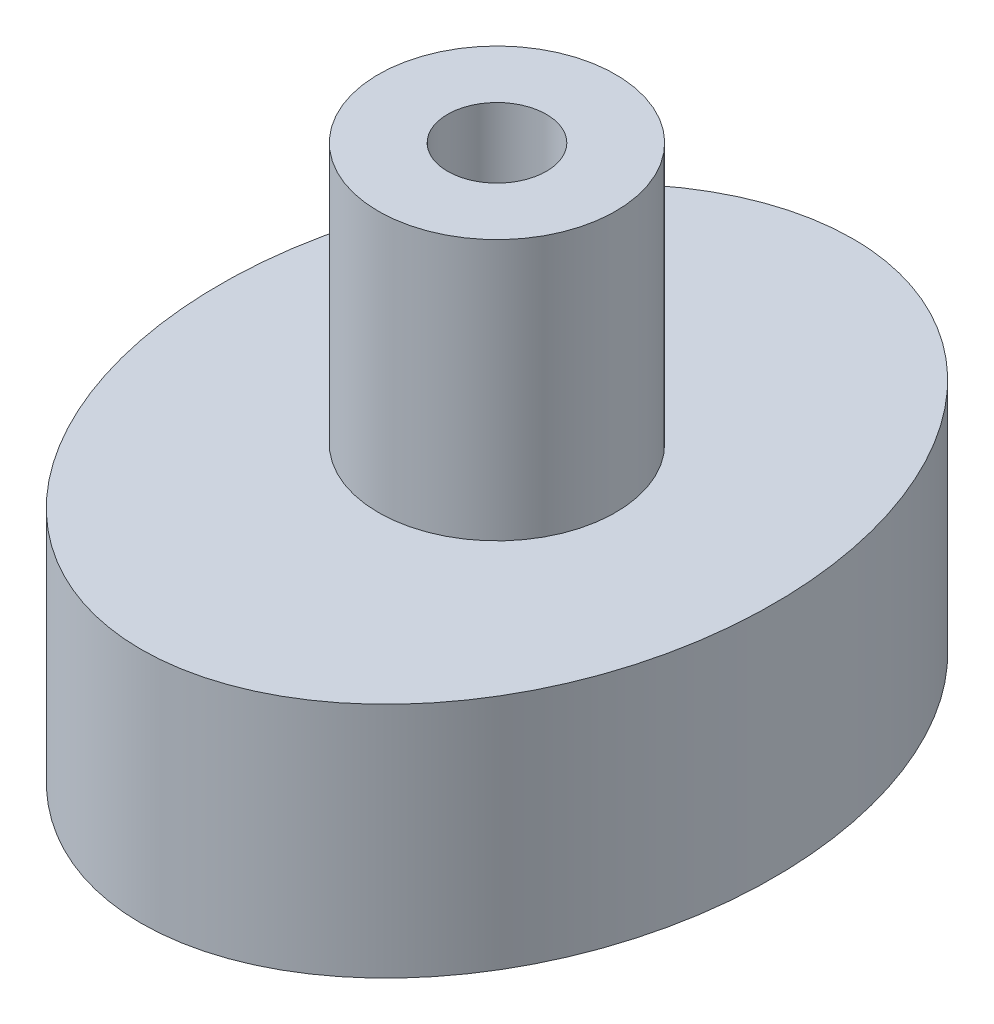
SolidWorks part; units mm, degrees
ref_plane "Front Plane" through (0, 0, 0) normal (0, 0, 1) x (1, 0, 0)
ref_plane "Top Plane" through (0, 0, 0) normal (0, 1, 0) x (1, 0, 0)
ref_plane "Right Plane" through (0, 0, 0) normal (1, 0, 0) x (0, 0, -1)
sketch "Sketch1" plane through (0, 0, 0) normal (0, 1, 0) x (1, 0, 0)
  circle A0 centre (0, 0) radius 25.4
  dimension "D1" = 50.8
extrude "Boss-Extrude1" add sketch "Sketch1" along normal blind 5.842
sketch "Sketch2" plane through (0, 5.842, 0) normal (0, 1, 0) x (1, 0, 0)
  ellipse E0 centre (0, 0) end of major axis (0, 45.72) minor radius 35.56
  dimension "D1" = 91.44
  dimension "D2" = 71.12
extrude "Boss-Extrude2" add sketch "Sketch2" along normal blind 30.48
sketch "Sketch3" plane through (0, 36.322, 0) normal (0, 1, 0) x (1, 0, 0)
  circle A0 centre (0, 0) radius 15.24
  dimension "D1" = 30.48
extrude "Boss-Extrude3" add sketch "Sketch3" along normal blind 33.528
sketch "Sketch4" plane through (0, 0, 0) normal (0, 1, 0) x (1, 0, 0)
  circle A0 centre (0, 0) radius 6.35
  dimension "D1" = 12.7
extrude "Cut-Extrude2" cut sketch "Sketch4" against normal through all and the other way through all
